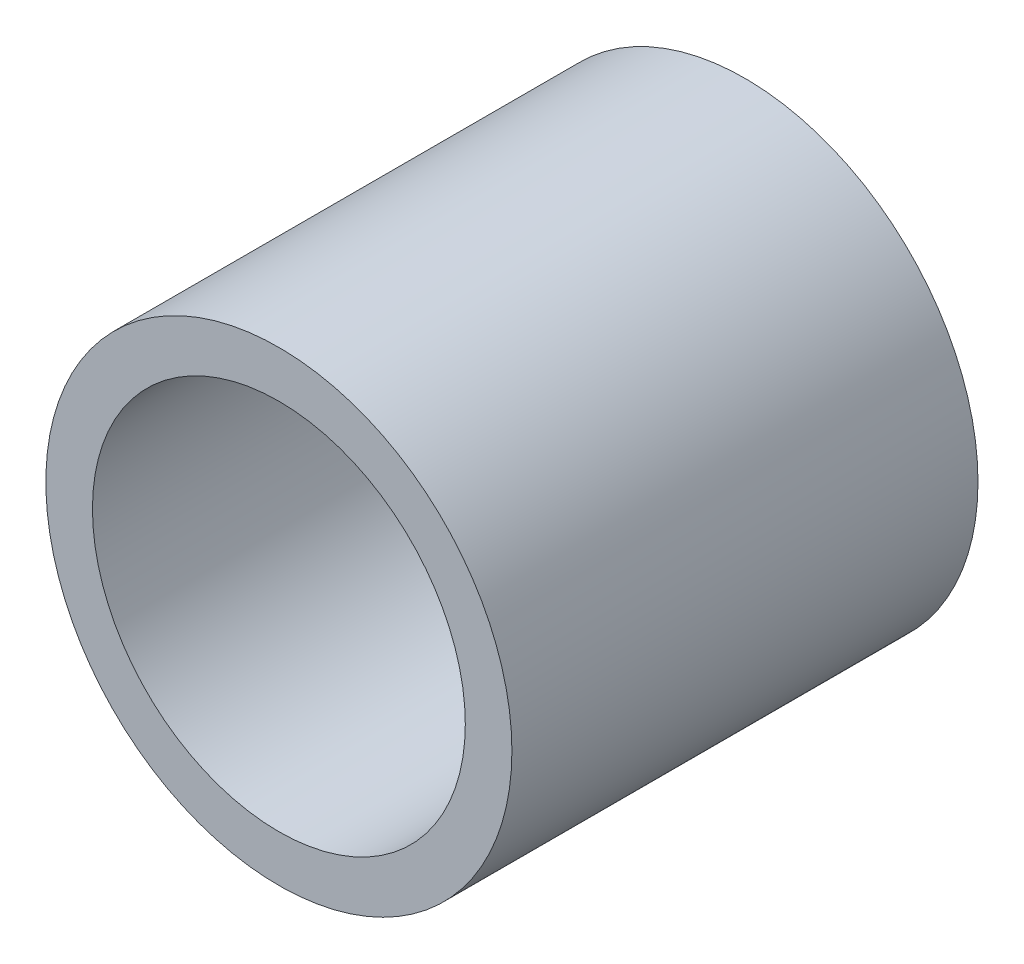
SolidWorks part; units mm, degrees
ref_plane "Front" through (0, 0, 0) normal (0, 0, 1) x (1, 0, 0)
ref_plane "Top" through (0, 0, 0) normal (0, 1, 0) x (1, 0, 0)
ref_plane "Right" through (0, 0, 0) normal (1, 0, 0) x (0, 0, -1)
sketch "Skizze1" plane through (0, 0, 0) normal (0, 0, 1) x (1, 0, 0)
  circle A0 centre (0, 0) radius 2.2
  circle A1 centre (0, 0) radius 2.75
  dimension "D1" = 5.5
  dimension "D2" = 4.4
extrude "Aufsatz-Linear austragen1" add sketch "Skizze1" along normal blind 5.5
